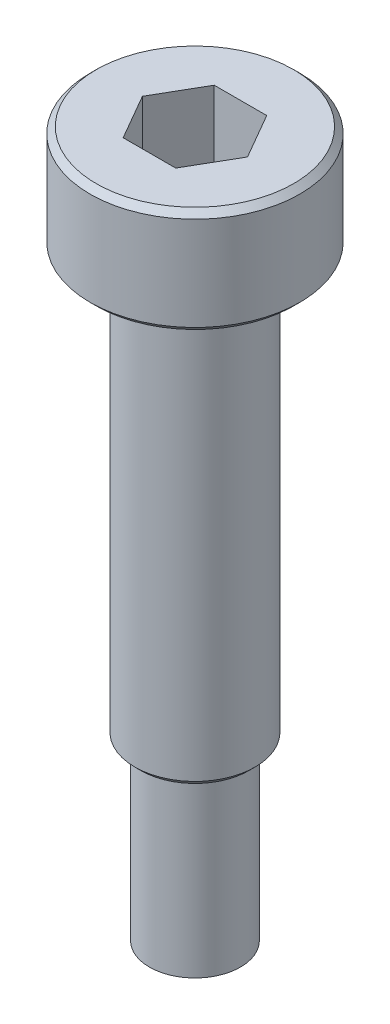
SolidWorks part; units mm, degrees
material "AISI 304"
ref_plane "Front Plane" through (0, 0, 0) normal (0, 0, 1) x (1, 0, 0)
ref_plane "Top Plane" through (0, 0, 0) normal (0, 1, 0) x (1, 0, 0)
ref_plane "Right Plane" through (0, 0, 0) normal (1, 0, 0) x (0, 0, -1)
sketch "Sketch1" plane through (0, 0, 0) normal (0, 0, 1) x (1, 0, 0)
  line L0 (0, 0) -> (1.5, 0)
  line L1 (1.5, 0) -> (1.5, 5.75)
  line L2 (1.5, 5.75) -> (1.98, 5.75)
  line L3 (1.98, 5.75) -> (1.98, 19.75)
  line L6 (1.98, 19.75) -> (3.455, 19.75)
  line L7 (3.455, 19.75) -> (3.455, 23.24)
  line L8 (3.455, 23.24) -> (0, 23.24)
  line L9 (0, 23.24) -> (0, 0)
  dimension "D1" = 3.49
  dimension "D2" = 14
  dimension "D3" = 5.75
  dimension "D4" = 1.5
  dimension "D5" = 1.98
  dimension "D6" = 3.455
revolve "Revolve1" add sketch "Sketch1" angle 360 about L9
cosmetic thread "Cosmetic Thread1" parameters "D2"=2.439
sketch "Sketch2" plane through (0, 23.24, 0) normal (0, 1, 0) x (1, 0, 0)
  line L0 (0, 0) -> (1.7321, 0) construction
  line L1 (1.7321, 0) -> (0.866, 1.5)
  line L2 (0.866, 1.5) -> (-0.866, 1.5)
  line L3 (-0.866, 1.5) -> (-1.7321, 0)
  line L4 (-1.7321, 0) -> (-0.866, -1.5)
  line L5 (-0.866, -1.5) -> (0.866, -1.5)
  line L6 (0.866, -1.5) -> (1.7321, 0)
  circle A0 centre (0, 0) radius 1.5 construction
  dimension "D1" = 3
extrude "Cut-Extrude1" cut sketch "Sketch2" against normal blind 2.4
chamfer "Chamfer1" distance 0.2 angle 45 3 edges at (0, 5.75, 1.98) (0, 19.75, 3.455) (0, 23.24, 3.455)
equation "\"D4@Sketch1\"=3/2"
equation "\"D5@Sketch1\"=3.96/2"
equation "\"D6@Sketch1\"=6.91/2"
equation "\"Length\" = 14"
equation "\"D2@Sketch1\"=\"Length\""
